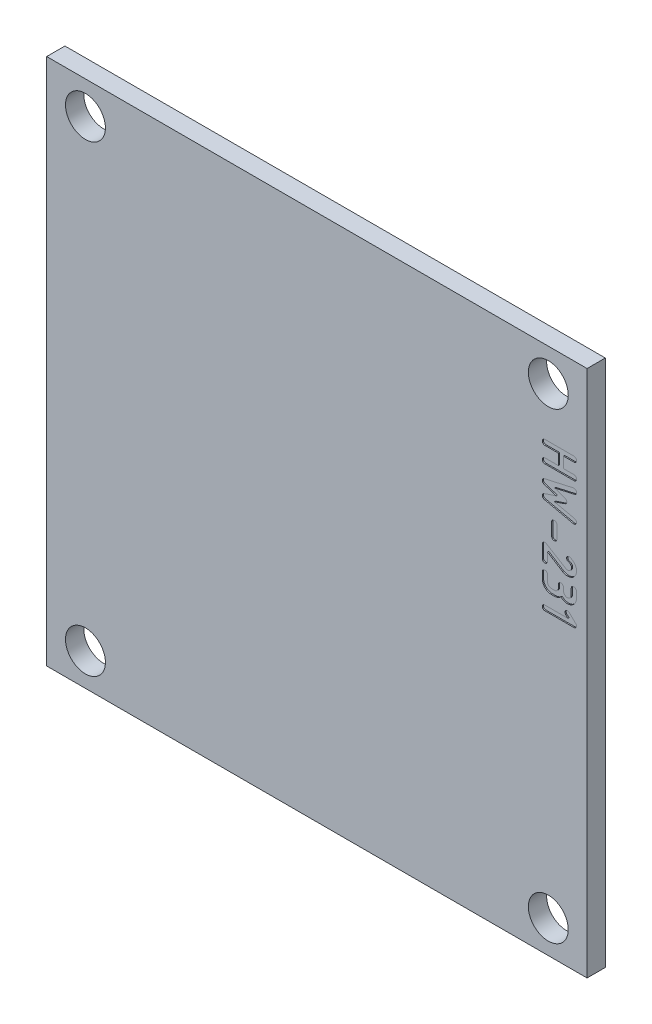
SolidWorks part; units mm, degrees
ref_plane "Front Plane" through (0, 0, 0) normal (0, 0, 1) x (1, 0, 0)
ref_plane "Top Plane" through (0, 0, 0) normal (0, 1, 0) x (1, 0, 0)
ref_plane "Right Plane" through (0, 0, 0) normal (1, 0, 0) x (0, 0, -1)
sketch "Sketch1" plane through (0, 0, 0) normal (0, 0, 1) x (1, 0, 0)
  line L1 (-23.7, -23.15) -> (23.7, -23.15)
  line L2 (-23.7, -23.15) -> (-23.7, 23.15)
  line L3 (-23.7, 23.15) -> (23.7, 23.15)
  line L4 (23.7, -23.15) -> (23.7, 23.15)
  line L5 (-23.7, -23.15) -> (23.7, 23.15) construction
  line L6 (-23.7, 23.15) -> (23.7, -23.15) construction
  point P0 (0, 0)
  dimension "D1" = 46.3
  dimension "D2" = 47.4
extrude "Boss-Extrude1" add sketch "Sketch1" along normal blind 1.6
sketch "Sketch2" plane through (0, 0, 0) normal (0, 0, 1) x (1, 0, 0)
  line L1 (-20.3, -20.3) -> (20.3, -20.3) construction
  line L2 (-20.3, -20.3) -> (-20.3, 20.3) construction
  line L3 (-20.3, 20.3) -> (20.3, 20.3) construction
  line L4 (20.3, -20.3) -> (20.3, 20.3) construction
  line L5 (-20.3, -20.3) -> (20.3, 20.3) construction
  line L6 (-20.3, 20.3) -> (20.3, -20.3) construction
  circle A0 centre (-20.3, 20.3) radius 1.75
  circle A1 centre (20.3, 20.3) radius 1.75
  circle A2 centre (20.3, -20.3) radius 1.75
  circle A3 centre (-20.3, -20.3) radius 1.75
  point P0 (0, 0)
  dimension "D3" = 3.5
  dimension "D1" = 40.6
  dimension "D2" = 40.6
extrude "Cut-Extrude2" cut sketch "Sketch2" along normal through all
sketch "Sketch3" plane through (0, 0, 1.6) normal (0, 0, 1) x (1, 0, 0)
  line L0 (19.77, 16.1986) -> (19.77, 2.153) construction
  text T0 "HW-231" font "DS ISO 1" height 3
extrude "label" cut sketch "Sketch3" against normal blind 0.1
